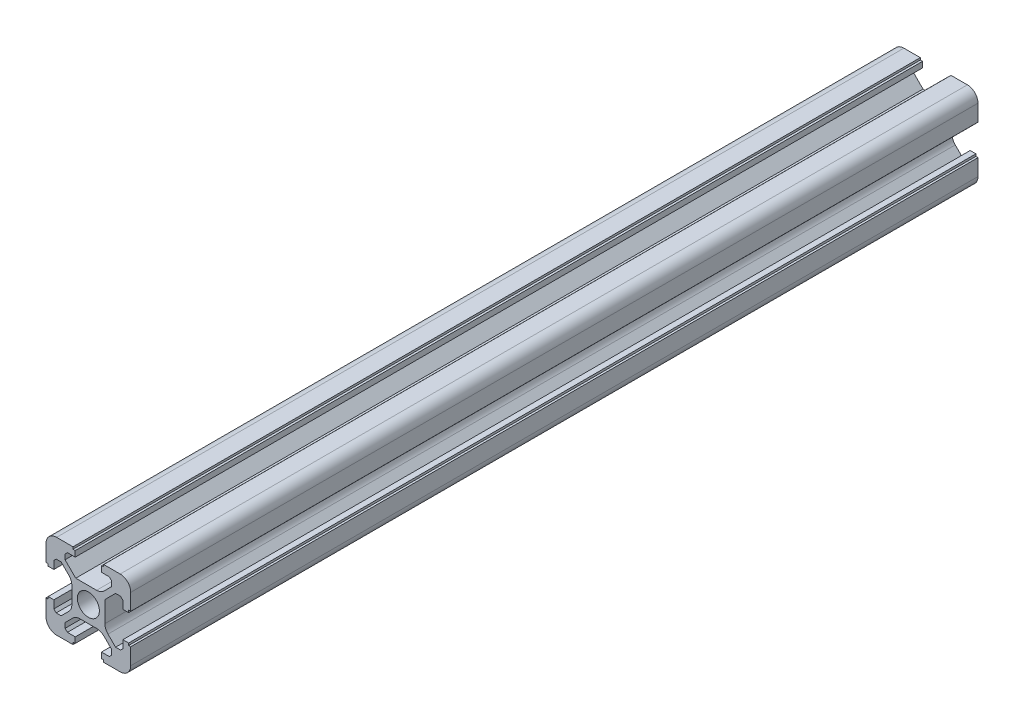
SolidWorks part; units mm, degrees
material "6061 Alloy"
ref_plane "Front Plane" through (0, 0, 0) normal (0, 0, 1) x (1, 0, 0)
ref_plane "Top Plane" through (0, 0, 0) normal (0, 1, 0) x (1, 0, 0)
ref_plane "Right Plane" through (0, 0, 0) normal (1, 0, 0) x (0, 0, -1)
sketch "Sketch1" plane through (0, 0, 0) normal (0, 0, 1) x (1, 0, 0)
  line L0 (-3.1, 10) -> (3.1, 10)
  line L1 (-10, 10) -> (10, 10)
  line L2 (-10, 10) -> (-10, -10)
  line L3 (-10, -10) -> (10, -10)
  line L4 (10, 10) -> (10, -10)
  line L5 (-10, 10) -> (10, -10) construction
  line L6 (-10, -10) -> (10, 10) construction
  line L7 (-5.5, 5.5) -> (5.5, 5.5)
  line L8 (-5.5, 5.5) -> (-5.5, -5.5)
  line L9 (-5.5, -5.5) -> (5.5, -5.5)
  line L10 (5.5, 5.5) -> (5.5, -5.5)
  line L11 (-5.5, 5.5) -> (5.5, -5.5) construction
  line L12 (-5.5, -5.5) -> (5.5, 5.5) construction
  line L13 (-8.15, -8.15) -> (8.15, -8.15)
  line L14 (-8.15, -8.15) -> (-8.15, 8.15)
  line L15 (-8.15, 8.15) -> (8.15, 8.15)
  line L16 (8.15, -8.15) -> (8.15, 8.15)
  line L17 (-8.15, -8.15) -> (8.15, 8.15) construction
  line L18 (-8.15, 8.15) -> (8.15, -8.15) construction
  line L19 (10, 3.1) -> (8.15, 3.1)
  line L20 (-3.1, 10) -> (3.1, 10)
  line L21 (-3.1, 10) -> (-3.1, 8.15)
  line L22 (-3.1, 8.15) -> (3.1, 8.15)
  line L23 (3.1, 10) -> (3.1, 8.15)
  line L24 (10, -3.1) -> (8.15, -3.1)
  line L25 (3.1, -10) -> (3.1, -8.15)
  line L26 (-3.1, -10) -> (-3.1, -8.15)
  line L27 (-10, -3.1) -> (-8.15, -3.1)
  line L28 (-10, 3.1) -> (-8.15, 3.1)
  circle A0 centre (0, 0) radius 2.6
  point P0 (0, 0)
  point P19 (0, 10)
  point P36 (0, 0)
  dimension "D3" = 5.2
  dimension "D1" = 20
  dimension "D2" = 20
  dimension "D4" = 11
  dimension "D5" = 11
  dimension "D6" = 1.85
  dimension "D7" = 1.85
  dimension "D8" = 6.2
  dimension "D9" = 4
extrude "Boss-Extrude1" add sketch "Sketch1" along normal blind 200 contours L2 L28 L14 L15 L21 L1 | L1 L23 L15 L16 L19 L4 | L13 L16 L15 L14 L7 L10 L9 L8 | L25 L3 L4 L24 L16 L13 | L27 L2 L3 L26 L13 L14 | L10 L7 L8 L9 A0
sketch "Sketch2" plane through (0, 0, 200) normal (0, 0, 1) x (1, 0, 0)
  line L0 (-10, 10) -> (-3.1, 10) construction
  line L1 (-3.9, 3.9) -> (3.9, 3.9)
  line L2 (-3.9, 3.9) -> (-3.9, -3.9)
  line L3 (-3.9, -3.9) -> (3.9, -3.9)
  line L4 (3.9, 3.9) -> (3.9, -3.9)
  line L5 (-3.9, 3.9) -> (3.9, -3.9) construction
  line L6 (-3.9, -3.9) -> (3.9, 3.9) construction
  line L7 (-10, -3.1) -> (-10, -10) construction
  line L8 (8.15, 5.5) -> (8.15, -5.5)
  line L9 (-5.5, -8.15) -> (5.5, -8.15)
  line L10 (-5.5, -8.15) -> (-5.5, 8.15)
  line L11 (-5.5, 8.15) -> (5.5, 8.15)
  line L12 (5.5, -8.15) -> (5.5, 8.15)
  line L13 (-5.5, -8.15) -> (5.5, 8.15) construction
  line L14 (-5.5, 8.15) -> (5.5, -8.15) construction
  line L15 (-8.15, 5.5) -> (8.15, 5.5)
  line L16 (-8.15, -5.5) -> (8.15, -5.5)
  line L17 (-8.15, 5.5) -> (-8.15, -5.5)
  line L18 (5.5, -8.15) -> (-5.5, -8.15)
  line L19 (5.5, 8.15) -> (5.5, -8.15)
  line L20 (-5.5, 8.15) -> (-5.5, -8.15)
  line L21 (5.5, 8.15) -> (-5.5, 8.15)
  line L22 (-8.15, -5.5) -> (-8.15, 5.5)
  line L23 (8.15, -5.5) -> (-8.15, -5.5)
  line L24 (8.15, 5.5) -> (-8.15, 5.5)
  line L25 (8.15, -5.5) -> (8.15, 5.5)
  line L26 (-10, 3.1) -> (-3.1, 10)
  line L27 (-6.55, 6.55) -> (-3.9, 3.9)
  line L28 (-6.0904, 7.0096) -> (-7.0096, 6.0904)
  line L29 (-7.0096, 6.0904) -> (-3.9, 2.9808)
  line L30 (-6.0904, 7.0096) -> (-2.9808, 3.9)
  line L31 (6.0904, 7.0096) -> (2.9808, 3.9)
  line L32 (7.0096, 6.0904) -> (3.9, 2.9808)
  line L33 (3.1, 10) -> (10, 3.1)
  line L34 (7.0096, -6.0904) -> (3.9, -2.9808)
  line L35 (6.0904, -7.0096) -> (2.9808, -3.9)
  line L36 (10, -3.1) -> (3.1, -10)
  line L37 (-6.0904, -7.0096) -> (-2.9808, -3.9)
  line L38 (-7.0096, -6.0904) -> (-3.9, -2.9808)
  line L39 (-3.1, -10) -> (-10, -3.1)
  point P0 (0, 0)
  point P10 (0, 0)
  point P19 (0, 0)
  point P24 (0, 0)
  point P29 (0, 0)
  point P34 (0, 0)
  point P40 (-6.55, 6.55)
  point P63 (0, 0)
  line M8 (-3.1, -8.15) -> (3.1, -8.15)
  line M13 (8.15, -3.1) -> (8.15, 3.1)
  line M18 (3.1, 8.15) -> (-3.1, 8.15)
  line M23 (-8.15, 3.1) -> (-8.15, -3.1)
  dimension "D1" = 6.1
  dimension "D2" = 6.1
  dimension "D3" = 11
  dimension "D4" = 1.85
  dimension "D6" = 1.3
  dimension "D7" = 90
  dimension "D8" = 90
  dimension "D5" = 4
  dimension "D9" = 4
extrude "Cut-Extrude2" cut sketch "Sketch2" against normal through all contours L39 L23 L38 L20 L29 L24 L26 L22 L17 M23 | L20 L38 L2 L29 | L33 L11 L21 L26 L20 L30 L24 L31 L19 M18 | L31 L24 L30 L1 | L36 L8 L25 L33 L24 L32 L19 L34 L23 M13 | L34 L19 L32 L4 | L39 L18 L9 L36 L19 L35 L23 L37 L20 M8 | L37 L23 L35 L3
fillet "Fillet1" radius 2.5 4 edges at (10, 10, 100) (-10, -10, 100) (10, -10, 100) (-10, 10, 100)
fillet "Fillet2" radius 2.5 6 edges at (3.9, -2.9808, 100) (2.9808, -3.9, 100) (-2.9808, -3.9, 100) (-3.9, -2.9808, 100) (-3.9, 2.9808, 100) (2.9808, 3.9, 100)
sketch "Sketch3" plane through (0, 0, 200) normal (0, 0, 1) x (1, 0, 0)
  line L0 (0, 0) -> (0, 10) construction
  line L1 (-3.1, 10) -> (3.1, 10) construction
  line L2 (9.5, 3.625) -> (9.5, -3.625)
  line L3 (-3.625, 9.5) -> (3.625, 9.5)
  line L4 (-3.625, 9.5) -> (-3.625, 10.5)
  line L5 (-3.625, 10.5) -> (3.625, 10.5)
  line L6 (3.625, 9.5) -> (3.625, 10.5)
  line L7 (-3.625, 9.5) -> (3.625, 10.5) construction
  line L8 (-3.625, 10.5) -> (3.625, 9.5) construction
  line L9 (9.5, -3.625) -> (10.5, -3.625)
  line L10 (10.5, 3.625) -> (10.5, -3.625)
  line L11 (9.5, 3.625) -> (10.5, 3.625)
  line L12 (3.625, -9.5) -> (-3.625, -9.5)
  line L13 (-3.625, -9.5) -> (-3.625, -10.5)
  line L14 (3.625, -10.5) -> (-3.625, -10.5)
  line L15 (3.625, -9.5) -> (3.625, -10.5)
  line L16 (-9.5, -3.625) -> (-9.5, 3.625)
  line L17 (-9.5, 3.625) -> (-10.5, 3.625)
  line L18 (-10.5, -3.625) -> (-10.5, 3.625)
  line L19 (-9.5, -3.625) -> (-10.5, -3.625)
  point P26 (0, 0)
  dimension "D1" = 1
  dimension "D2" = 7.25
  dimension "D3" = 4
extrude "Cut-Extrude3" cut sketch "Sketch3" against normal through all
